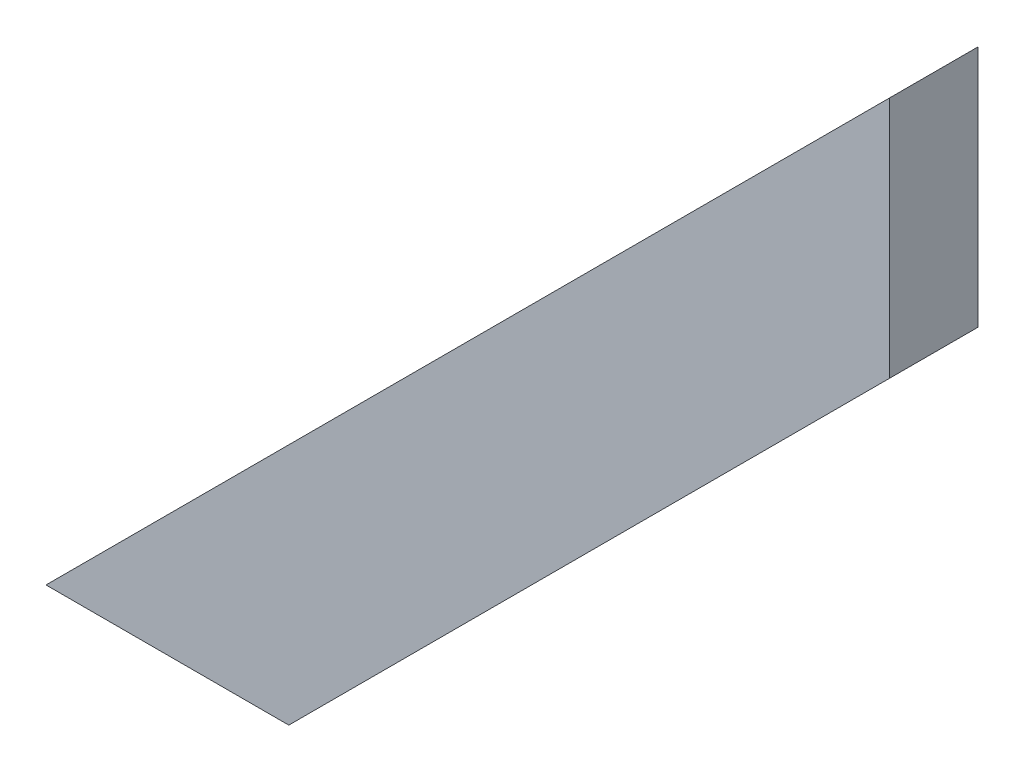
SolidWorks part; units mm, degrees
ref_plane "Front Plane" through (0, 0, 0) normal (0, 0, 1) x (1, 0, 0)
ref_plane "Top Plane" through (0, 0, 0) normal (0, 1, 0) x (1, 0, 0)
ref_plane "Right Plane" through (0, 0, 0) normal (1, 0, 0) x (0, 0, -1)
sketch "Sketch1" plane through (0, 0, 0) normal (0, 0, 1) x (1, 0, 0)
  line L6 (0, 0) -> (172, 172)
  line L7 (0, 0) -> (49.4975, 0)
  line L10 (172, 122.5025) -> (172, 172)
  line L11 (49.4975, 0) -> (172, 122.5025)
  dimension "D3" = 35
extrude "Boss-Extrude2" add sketch "Sketch1" along normal blind 18
